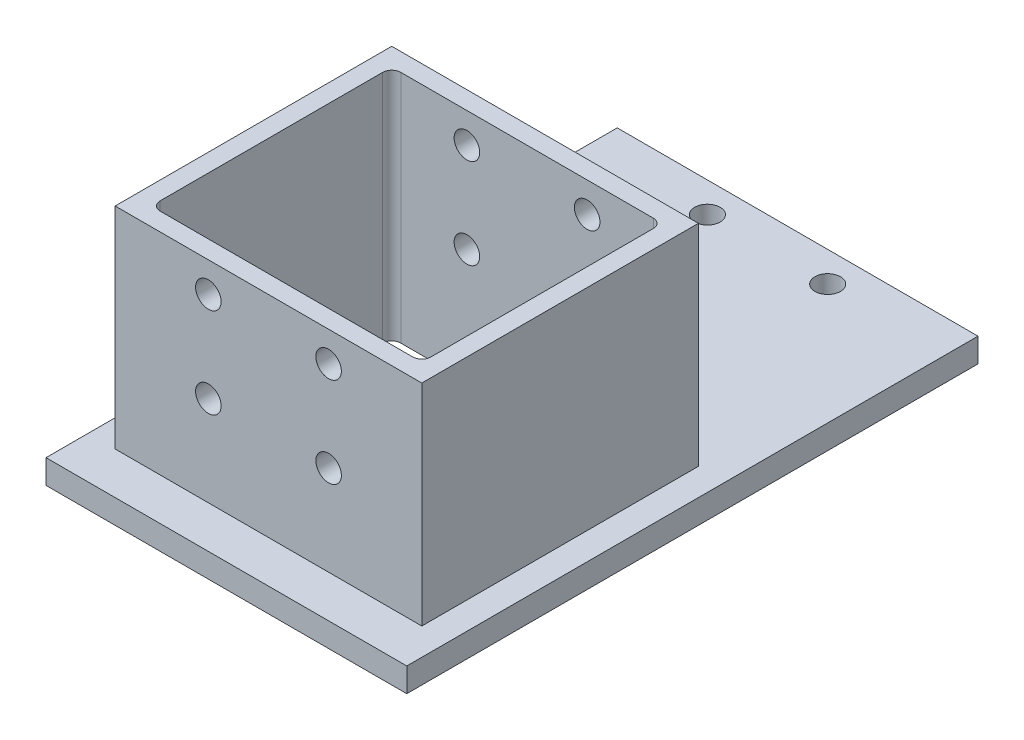
SolidWorks part; units mm, degrees
ref_plane "前视基准面" through (0, 0, 0) normal (0, 0, 1) x (1, 0, 0)
ref_plane "上视基准面" through (0, 0, 0) normal (0, 1, 0) x (1, 0, 0)
ref_plane "右视基准面" through (0, 0, 0) normal (1, 0, 0) x (0, 0, -1)
other "Configuration Table"
sketch "草图1" plane through (0, 0, 0) normal (0, 1, 0) x (1, 0, 0)
  line L0 (-54.6921, 0) -> (100.3573, 0) construction
  line L1 (-60, 95) -> (60, 95)
  line L2 (-60, 95) -> (-60, -95)
  line L3 (-60, -95) -> (60, -95)
  line L4 (60, 95) -> (60, -95)
  line L5 (0, 57.9444) -> (0, -53.6964) construction
  line L7 (-45, 5) -> (45, 5)
  line L8 (-45, 5) -> (-45, -75)
  line L9 (-45, -75) -> (45, -75)
  line L10 (45, 5) -> (45, -75)
  circle A0 centre (20, 85) radius 4.25
  circle A1 centre (20, 25) radius 4.25
  circle A2 centre (-20, 85) radius 4.25
  circle A3 centre (-20, 25) radius 4.25
  dimension "D1" = 8.5
  dimension "D2" = 20
  dimension "D3" = 60
  dimension "D4" = 10
  dimension "D5" = 90
  dimension "D6" = 120
  dimension "D7" = 80
  dimension "D8" = 20
  dimension "D9" = 20
extrude "凸台-拉伸1" add sketch "草图1" along normal blind 8
sketch "草图2" plane through (0, 8, 0) normal (0, 1, 0) x (1, 0, 0)
  line L0 (-45, -75) -> (45, -75) construction
  line L1 (-45, 5) -> (-45, -75) construction
  line L2 (45, 5) -> (-45, 5) construction
  line L3 (45, -75) -> (45, 5) construction
  line L4 (-45, -75) -> (45, -75)
  line L5 (-45, 5) -> (-45, -75)
  line L6 (45, 5) -> (-45, 5)
  line L7 (45, -75) -> (45, 5)
  line L9 (-51, 11) -> (51, 11)
  line L10 (-51, 11) -> (-51, -81)
  line L11 (-51, -81) -> (51, -81)
  line L12 (51, 11) -> (51, -81)
  dimension "D1" = 6
  dimension "D2" = 6
  dimension "D3" = 6
  dimension "D4" = 6
extrude "凸台-拉伸2" add sketch "草图2" along normal blind 70
sketch "草图3" plane through (0, 0, -11) normal (0, 0, -1) x (-1, 0, 0)
  line L0 (0, 63.1191) -> (0, -14.1025) construction
  line L1 (-51, 78) -> (51, 78) construction
  circle A0 centre (20, 68) radius 4.25
  circle A1 centre (20, 38) radius 4.25
  circle A2 centre (-20, 38) radius 4.25
  circle A3 centre (-20, 68) radius 4.25
  dimension "D2" = 8.5
  dimension "D1" = 20
  dimension "D3" = 10
  dimension "D4" = 30
extrude "切除-拉伸1" cut sketch "草图3" against normal through all
fillet "圆角1" radius 3 4 edges at (45, 39, 75) (-45, 39, 75) (-45, 39, -5) (45, 39, -5)
